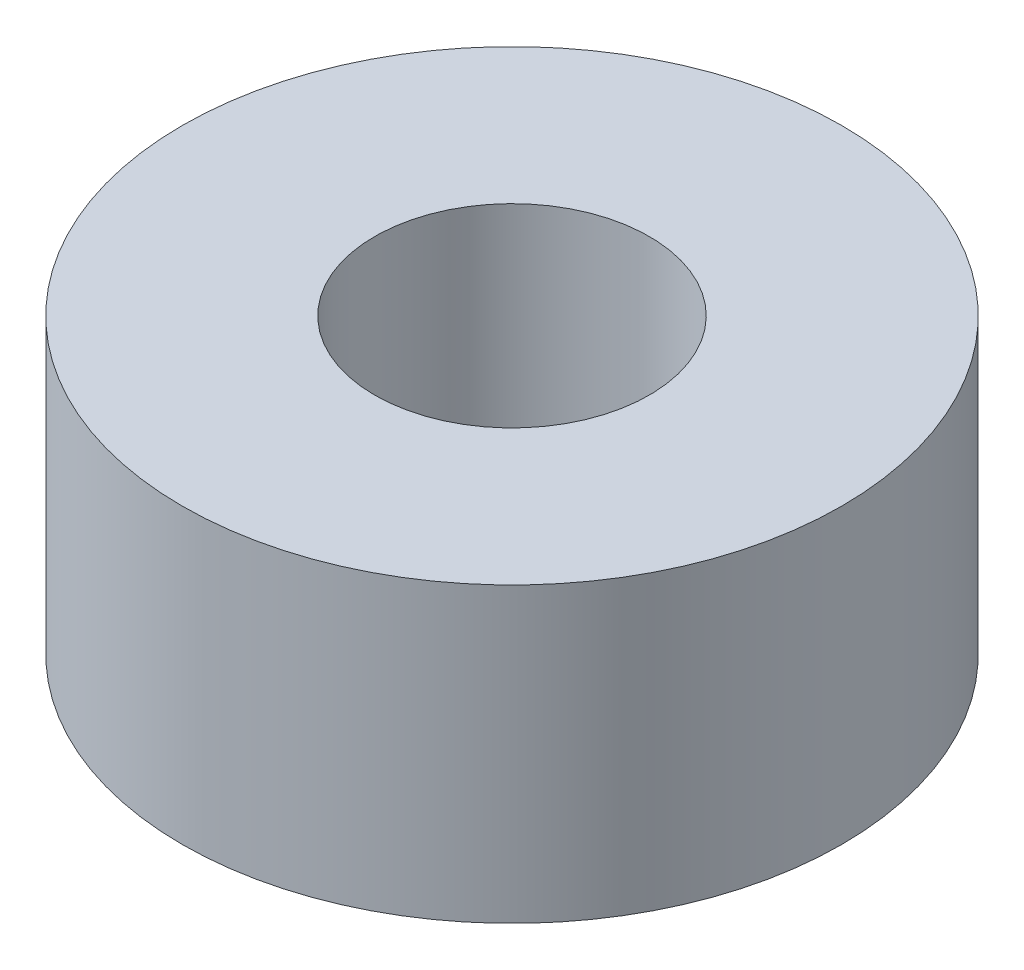
SolidWorks part; units mm, degrees
ref_plane "Front Plane" through (0, 0, 0) normal (0, 0, 1) x (1, 0, 0)
ref_plane "Top Plane" through (0, 0, 0) normal (0, 1, 0) x (1, 0, 0)
ref_plane "Right Plane" through (0, 0, 0) normal (1, 0, 0) x (0, 0, -1)
sketch "Sketch1" plane through (0, 0, 0) normal (0, 1, 0) x (1, 0, 0)
  circle A0 centre (0, 0) radius 7.5
  circle A1 centre (0, 0) radius 18
  dimension "D1" = 15
  dimension "D2" = 36
extrude "Boss-Extrude1" add sketch "Sketch1" along normal blind 16
